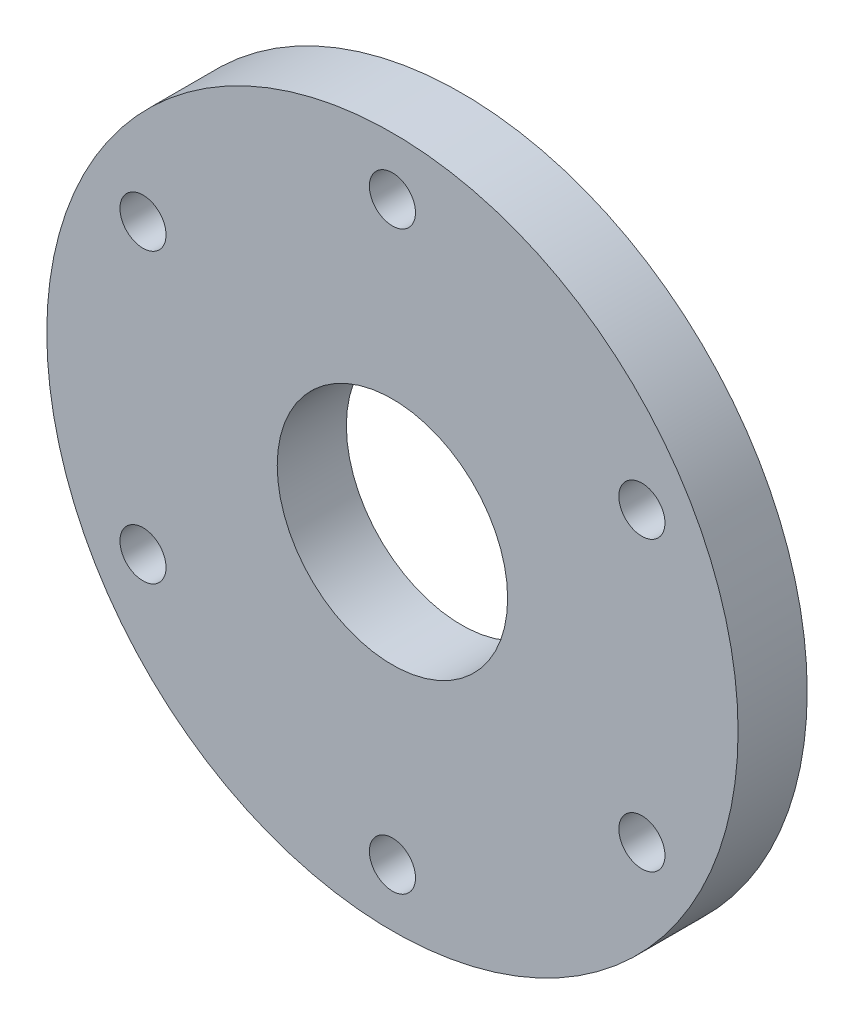
SolidWorks part; units mm, degrees
ref_plane "Front Plane" through (0, 0, 0) normal (0, 0, 1) x (1, 0, 0)
ref_plane "Top Plane" through (0, 0, 0) normal (0, 1, 0) x (1, 0, 0)
ref_plane "Right Plane" through (0, 0, 0) normal (1, 0, 0) x (0, 0, -1)
sketch "Sketch1" plane through (0, 0, 0) normal (0, 0, 1) x (1, 0, 0)
  circle A0 centre (0, 0) radius 30
  circle A1 centre (0, 0) radius 25 construction
  circle A2 centre (0, 0) radius 10
  circle A3 centre (0, 25) radius 2
  circle A4 centre (21.6506, 12.5) radius 2
  circle A5 centre (21.6506, -12.5) radius 2
  circle A6 centre (0, -25) radius 2
  circle A7 centre (-21.6506, -12.5) radius 2
  circle A8 centre (-21.6506, 12.5) radius 2
  point P19 (0, 0)
  dimension "D1" = 60
  dimension "D2" = 20
  dimension "D3" = 50
  dimension "D4" = 4
  dimension "D5" = 6
extrude "Boss-Extrude1" add sketch "Sketch1" along normal blind 6
